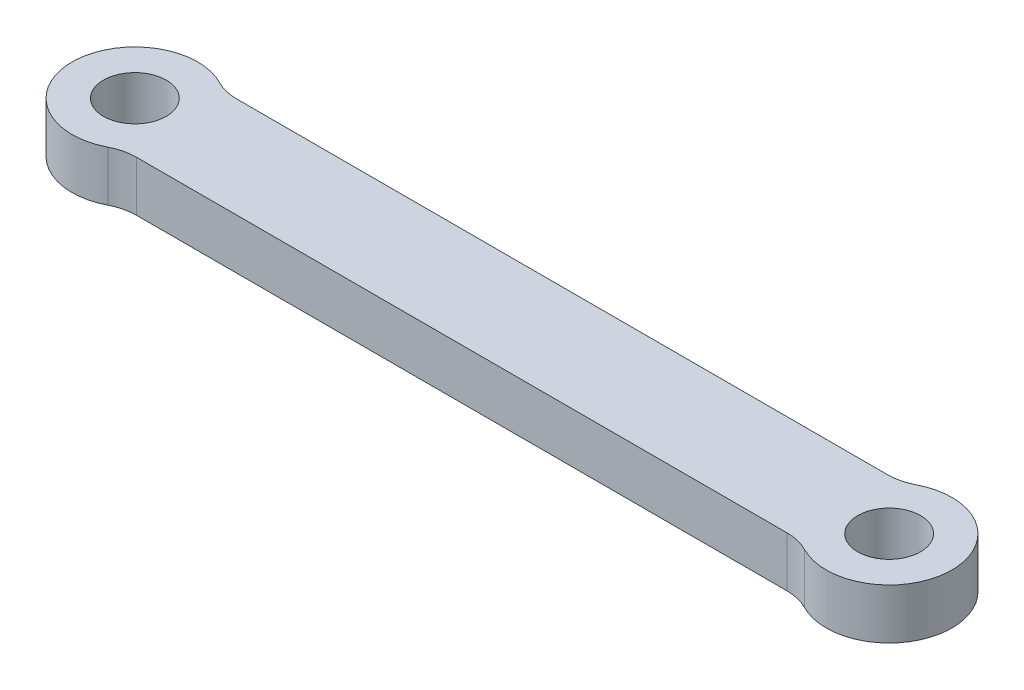
SolidWorks part; units mm, degrees
ref_plane "Front Plane" through (0, 0, 0) normal (0, 0, 1) x (1, 0, 0)
ref_plane "Top Plane" through (0, 0, 0) normal (0, 1, 0) x (1, 0, 0)
ref_plane "Right Plane" through (0, 0, 0) normal (1, 0, 0) x (0, 0, -1)
sketch "Sketch1" plane through (0, 0, 0) normal (0, 1, 0) x (1, 0, 0)
  line L0 (-25.8769, 4) -> (25.8769, 4)
  line L1 (-30.0509, -5) -> (-30, -5)
  line L2 (-25.8769, -4) -> (25.8769, -4)
  arc A0 (-27.7094, 4.4444) -> (-27.7094, -4.4444) centre (-30, 0) ccw
  arc A1 (27.7094, -4.4444) -> (27.7094, 4.4444) centre (30, 0) ccw
  circle A2 centre (-30, 0) radius 2.5
  circle A3 centre (30, 0) radius 2.5
  arc A4 (25.8769, -4) -> (27.7094, -4.4444) centre (25.8769, -8) cw
  arc A5 (25.8769, 4) -> (27.7094, 4.4444) centre (25.8769, 8) ccw
  arc A6 (-25.8769, -4) -> (-27.7094, -4.4444) centre (-25.8769, -8) ccw
  arc A7 (-25.8769, 4) -> (-27.7094, 4.4444) centre (-25.8769, 8) cw
  point P10 (27, -4)
  point P11 (-27, -4)
  dimension "D1" = 10
  dimension "D2" = 5
  dimension "D7" = 4
  dimension "D3" = 60
  dimension "D4" = 30
  dimension "D5" = 8
  dimension "D6" = 4
extrude "Boss-Extrude1" add sketch "Sketch1" along normal mid plane 4 contours L0 A7 A0 A6 L2 A4 A1 A5 A2 A3
